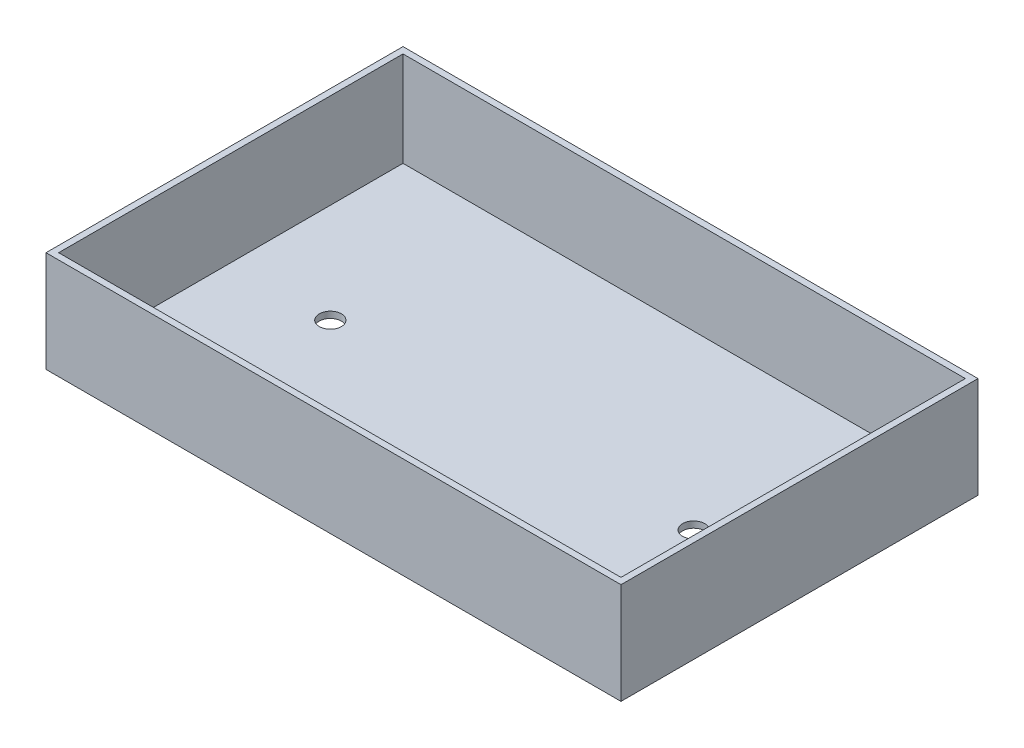
SolidWorks part; units mm, degrees
ref_plane "Front" through (0, 0, 0) normal (0, 0, 1) x (1, 0, 0)
ref_plane "Top" through (0, 0, 0) normal (0, 1, 0) x (1, 0, 0)
ref_plane "Right" through (0, 0, 0) normal (1, 0, 0) x (0, 0, -1)
sketch "Sketch1" plane through (0, 0, 0) normal (0, 1, 0) x (1, 0, 0)
  line L1 (0, 0) -> (91, 0)
  line L2 (0, 0) -> (0, 56.5)
  line L3 (0, 56.5) -> (91, 56.5)
  line L4 (91, 0) -> (91, 56.5)
  dimension "D1" = 56.5
  dimension "D2" = 91
extrude "Boss-Extrude1" add sketch "Sketch1" along normal blind 16
sketch "Sketch2" plane through (0, 16, 0) normal (0, 1, 0) x (1, 0, 0)
  line L0 (0, 56.5) -> (0, 0) construction
  line L1 (1, 1) -> (90, 1)
  line L2 (1, 1) -> (1, 55.5)
  line L3 (1, 55.5) -> (90, 55.5)
  line L4 (90, 1) -> (90, 55.5)
  line L5 (91, 56.5) -> (0, 56.5) construction
  line L6 (0, 0) -> (91, 0) construction
  line L7 (91, 0) -> (91, 56.5) construction
  dimension "D1" = 1
  dimension "D2" = 1
  dimension "D3" = 1
  dimension "D4" = 1
extrude "Cut-Extrude1" cut sketch "Sketch2" against normal blind 15
sketch "Sketch3" plane through (0, 1, 0) normal (0, 1, 0) x (1, 0, 0)
  line L0 (1, 28.25) -> (90, 28.25) construction
  line L1 (1, 55.5) -> (1, 1) construction
  line L2 (90, 1) -> (90, 55.5) construction
  line L3 (45.5, 28.25) -> (45.5, 5.9316) construction
  circle A0 centre (16.75, 28.25) radius 1.75
  circle A1 centre (74.25, 28.25) radius 1.75
  dimension "D2" = 3.5
  dimension "D1" = 57.5
extrude "Cut-Extrude2" cut sketch "Sketch3" against normal blind 15
